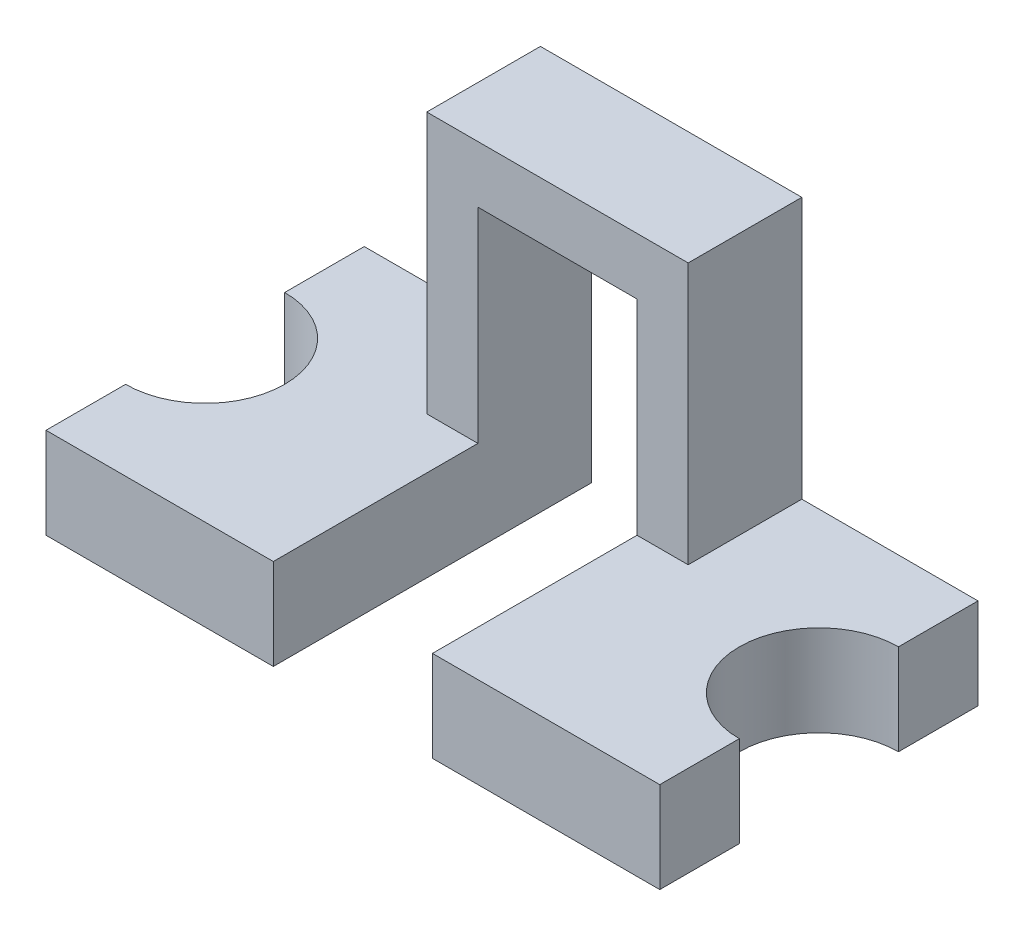
SolidWorks part; units mm, degrees
ref_plane "前视基准面" through (0, 0, 0) normal (0, 0, 1) x (1, 0, 0)
ref_plane "上视基准面" through (0, 0, 0) normal (0, 1, 0) x (1, 0, 0)
ref_plane "右视基准面" through (0, 0, 0) normal (1, 0, 0) x (0, 0, -1)
other "Configuration Table"
sketch "草图1" plane through (0, 0, 0) normal (0, 1, 0) x (1, 0, 0)
  line L0 (-378.6188, 0) -> (18552.319, 0) construction
  line L1 (0, -378.6188) -> (0, 18552.319) construction
  line L2 (27, 21) -> (27, 28)
  line L3 (7, 0) -> (27, 0)
  line L4 (7, 0) -> (7, 28)
  line L5 (7, 28) -> (27, 28)
  line L6 (27, 0) -> (27, 7)
  line L7 (-27, 0) -> (-27, 7)
  line L8 (-7, 28) -> (-27, 28)
  line L9 (-7, 0) -> (-7, 28)
  line L10 (-7, 0) -> (-27, 0)
  line L11 (-27, 21) -> (-27, 28)
  arc A0 (27, 21) -> (27, 7) centre (27, 14) ccw
  arc A1 (-27, 21) -> (-27, 7) centre (-27, 14) cw
  point P10 (33.0784, 16.476)
  point P13 (33.2626, 16.7984)
  point P21 (-27, 33.7154)
  dimension "D1" = 7
  dimension "D2" = 54
  dimension "D3" = 14
  dimension "D4" = 28
extrude "凸台-拉伸1" add sketch "草图1" along normal blind 8
sketch "草图2" plane through (0, 0, -28) normal (0, 0, -1) x (-1, 0, 0)
  line L0 (-11.5, 31) -> (11.5, 31)
  line L1 (-7, 8) -> (-11.5, 8)
  line L2 (-7, 8) -> (-7, 26)
  line L4 (-11.5, 8) -> (-11.5, 31)
  line L7 (-7, 26) -> (7, 26)
  line L9 (0, -1000) -> (0, 26) construction
  line L10 (0, 31) -> (0, 49000) construction
  line L11 (11.5, 8) -> (11.5, 31)
  line L12 (7, 8) -> (7, 26)
  line L13 (7, 8) -> (11.5, 8)
  line L14 (7, 0) -> (27, 0) construction
  dimension "D1" = 23
  dimension "D2" = 26
  dimension "D3" = 31
extrude "凸台-拉伸2" add sketch "草图2" against normal blind 10
